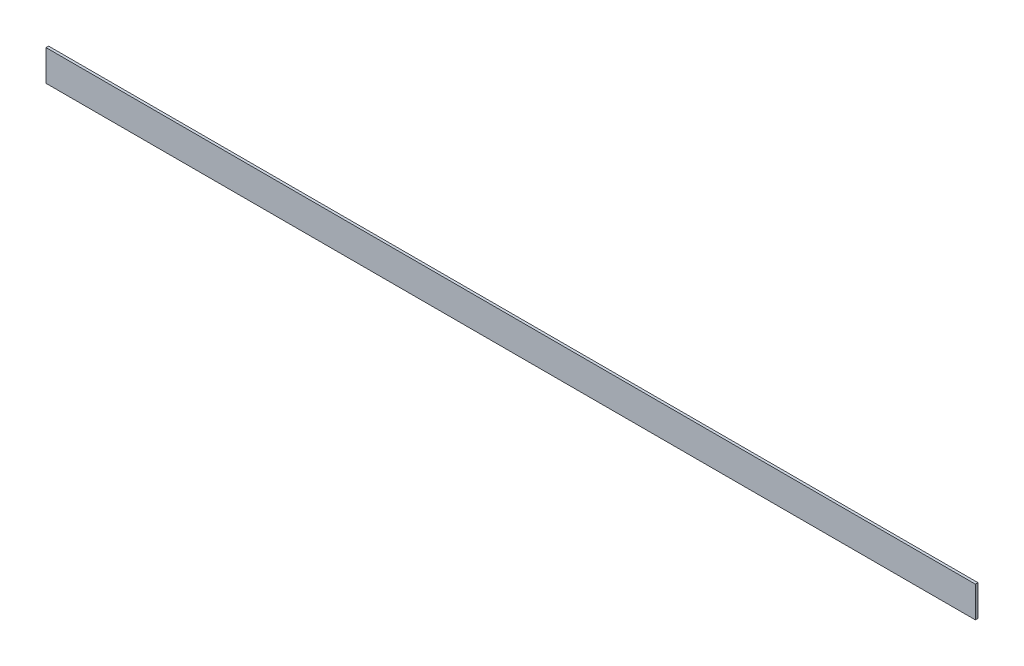
SolidWorks part; units mm, degrees
ref_plane "Płaszczyzna przednia" through (0, 0, 0) normal (0, 0, 1) x (1, 0, 0)
ref_plane "Płaszczyzna górna" through (0, 0, 0) normal (0, 1, 0) x (1, 0, 0)
ref_plane "Płaszczyzna prawa" through (0, 0, 0) normal (1, 0, 0) x (0, 0, -1)
sketch "Sketch1" plane through (0, 0, 0) normal (0, 0, 1) x (1, 0, 0)
  line L1 (0, 0) -> (360, 0)
  line L2 (0, 0) -> (0, 12)
  line L3 (0, 12) -> (360, 12)
  line L4 (360, 0) -> (360, 12)
  line L5 (0, 0) -> (360, 12) construction
  line L6 (0, 12) -> (360, 0) construction
  point P4 (180, 6)
  dimension "D1" = 360
  dimension "D2" = 12
extrude "Boss-Extrude1" add sketch "Sketch1" along normal blind 1
